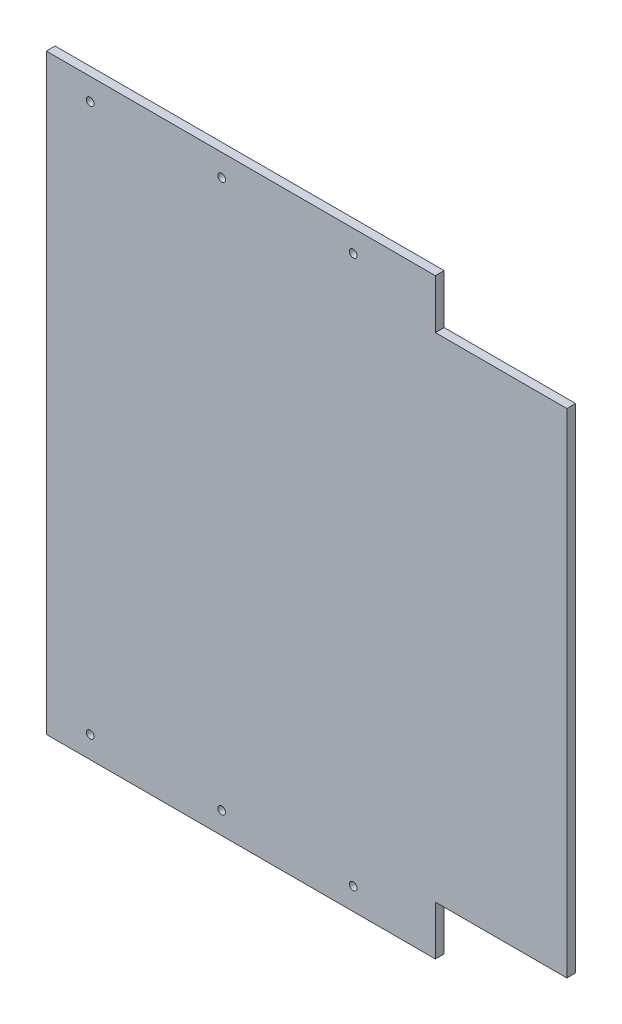
SolidWorks part; units mm, degrees
ref_plane "Plan de face" through (0, 0, 0) normal (0, 0, 1) x (1, 0, 0)
ref_plane "Plan de dessus" through (0, 0, 0) normal (0, 1, 0) x (1, 0, 0)
ref_plane "Plan de droite" through (0, 0, 0) normal (1, 0, 0) x (0, 0, -1)
sketch "Esquisse1" plane through (0, 0, 0) normal (0, 0, 1) x (1, 0, 0)
  line L1 (0, 0) -> (475, 0)
  line L2 (0, 0) -> (0, 540)
  line L3 (0, 540) -> (475, 540)
  line L4 (475, 0) -> (475, 540)
  dimension "D1" = 475
  dimension "D2" = 540
extrude "Boss.-Extru.1" add sketch "Esquisse1" along normal blind 8
sketch "Esquisse2" plane through (0, 0, 8) normal (0, 0, 1) x (1, 0, 0)
  line L0 (0, 520) -> (440, 520) construction
  line L1 (0, 540) -> (0, 0) construction
  line L2 (475, 0) -> (475, 540) construction
  line L3 (220, 540) -> (220, 520) construction
  line L4 (475, 540) -> (0, 540) construction
  line L5 (475, 270) -> (0, 270) construction
  line L6 (220, 0) -> (220, 20) construction
  line L7 (0, 20) -> (440, 20) construction
  circle A0 centre (160, 520) radius 3.5
  circle A1 centre (40, 520) radius 3.5
  circle A2 centre (400, 520) radius 3.5
  circle A3 centre (280, 520) radius 3.5
  circle A4 centre (280, 20) radius 3.5
  circle A5 centre (400, 20) radius 3.5
  circle A6 centre (40, 20) radius 3.5
  circle A7 centre (160, 20) radius 3.5
  point P32 (0, 0)
  point P33 (250, 513.2576)
  point P34 (0, 0)
  point P35 (224.9571, 520)
  dimension "D2" = 120
  dimension "D3" = 120
  dimension "D4" = 7
  dimension "D1" = 20
  dimension "D5" = 220
extrude "Enlèv. mat.-Extru.1" cut sketch "Esquisse2" against normal through all and the other way through all
sketch "Esquisse3" plane through (0, 0, 8) normal (0, 0, 1) x (1, 0, 0)
  line L0 (475, 270) -> (0, 270) construction
  line L1 (475, 540) -> (355, 540)
  line L2 (475, 540) -> (475, 495)
  line L3 (475, 495) -> (355, 495)
  line L4 (355, 540) -> (355, 495)
  line L5 (475, 0) -> (475, 540) construction
  line L6 (355, 0) -> (355, 45)
  line L7 (475, 45) -> (355, 45)
  line L8 (475, 0) -> (475, 45)
  line L9 (475, 0) -> (355, 0)
  dimension "D1" = 45
  dimension "D2" = 120
extrude "Enlèv. mat.-Extru.2" cut sketch "Esquisse3" against normal through all both and the other way through all
